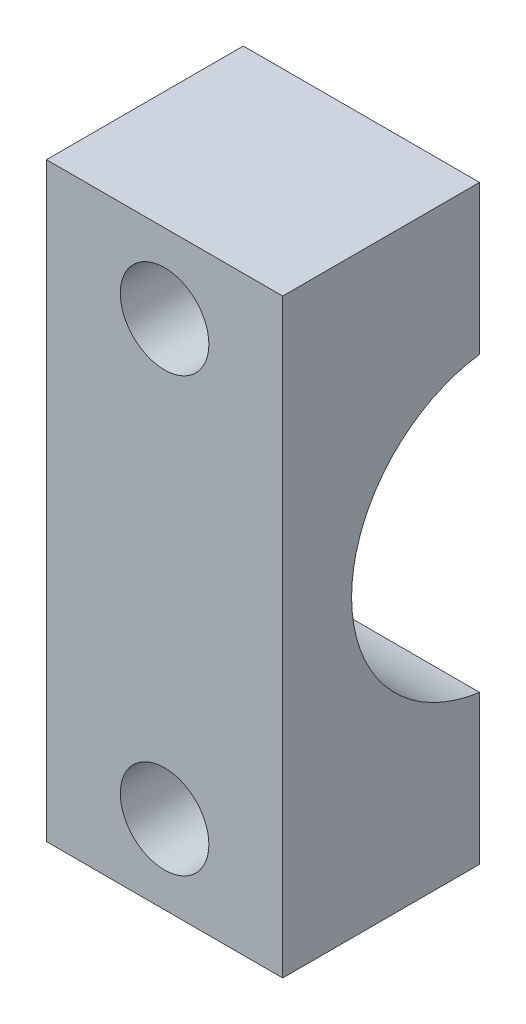
SolidWorks part; units mm, degrees
material "Printed PLA"
ref_plane "Front Plane" through (0, 0, 0) normal (0, 0, 1) x (1, 0, 0)
ref_plane "Top Plane" through (0, 0, 0) normal (0, 1, 0) x (1, 0, 0)
ref_plane "Right Plane" through (0, 0, 0) normal (1, 0, 0) x (0, 0, -1)
sketch "Sketch1" plane through (0, 0, 0) normal (1, 0, 0) x (0, 0, -1)
  line L0 (-1, 7.433) -> (-1, 15)
  line L1 (-1, 15) -> (-11, 15)
  line L2 (-11, 15) -> (-11, -15)
  line L3 (-11, -15) -> (-1, -15)
  line L4 (-1, -15) -> (-1, -7.433)
  arc A0 (-1, 7.433) -> (-1, -7.433) centre (0, 0) ccw
  dimension "D2" = 15
  dimension "D1" = 30
  dimension "D3" = 1
  dimension "D4" = 10
extrude "Boss-Extrude1" add sketch "Sketch1" against normal mid plane 12
sketch "Sketch2" plane through (0, 0, 11) normal (0, 0, 1) x (1, 0, 0)
  line L0 (0, -11) -> (0, 11) construction
  circle A0 centre (0, 11) radius 2.25
  circle A1 centre (0, -11) radius 2.25
  dimension "D2" = 4.5
  dimension "D1" = 22
extrude "Cut-Extrude1" cut sketch "Sketch2" against normal through all
